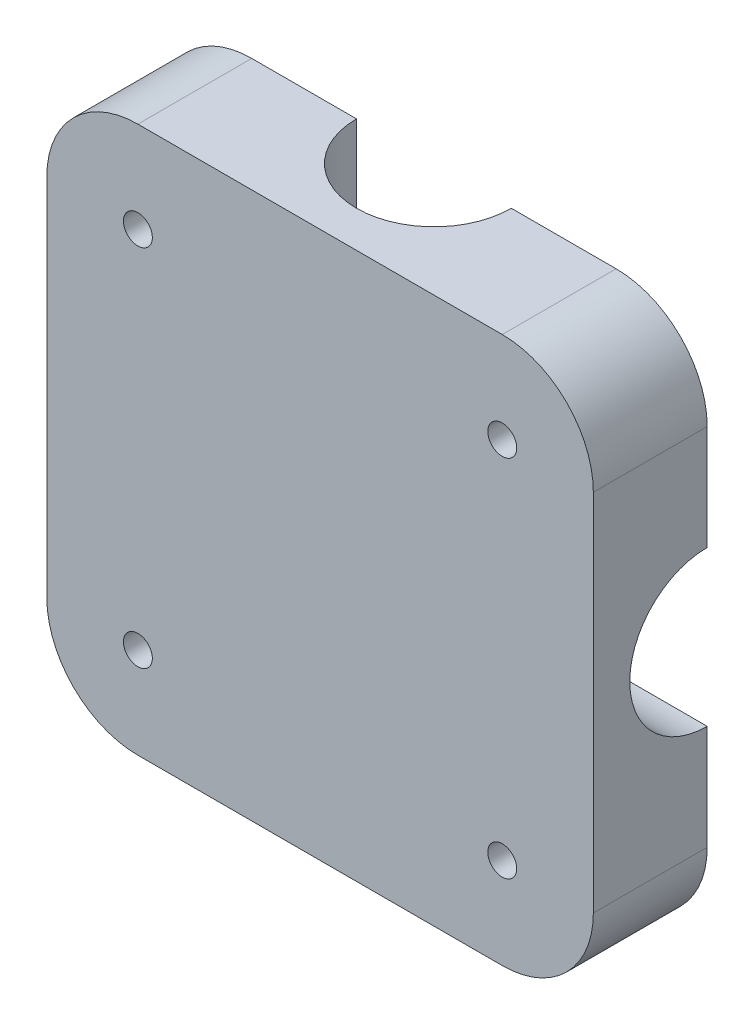
SolidWorks part; units mm, degrees
ref_plane "Alzado" through (0, 0, 0) normal (0, 0, 1) x (1, 0, 0)
ref_plane "Planta" through (0, 0, 0) normal (0, 1, 0) x (1, 0, 0)
ref_plane "Vista lateral" through (0, 0, 0) normal (1, 0, 0) x (0, 0, -1)
sketch "Croquis1" plane through (0, 0, 0) normal (0, 0, 1) x (1, 0, 0)
  line L1 (-20, -30) -> (20, -30)
  line L2 (-30, -20) -> (-30, 20)
  line L3 (-20, 30) -> (20, 30)
  line L4 (30, -20) -> (30, 20)
  line L5 (-30, -30) -> (30, 30) construction
  line L6 (-30, 30) -> (30, -30) construction
  arc A0 (20, 30) -> (30, 20) centre (20, 20) cw
  arc A1 (20, -30) -> (30, -20) centre (20, -20) ccw
  arc A2 (-20, -30) -> (-30, -20) centre (-20, -20) cw
  arc A3 (-30, 20) -> (-20, 30) centre (-20, 20) cw
  point P0 (0, 0)
  dimension "D3" = 10
  dimension "D1" = 60
  dimension "D2" = 60
extrude "Saliente-Extruir1" add sketch "Croquis1" along normal blind 12.5
sketch "Croquis2" plane through (0, 0, 0) normal (0, 1, 0) x (1, 0, 0)
  circle A0 centre (0, 0) radius 8.5
  dimension "D1" = 17
extrude "Cortar-Extruir1" cut sketch "Croquis2" against normal mid plane 82.5
sketch "Croquis3" plane through (-30, 0, 0) normal (-1, 0, 0) x (0, 0, 1)
  circle A0 centre (0, 0) radius 8.5
  dimension "D1" = 17
extrude "Cortar-Extruir2" cut sketch "Croquis3" against normal blind 82.5
sketch "Croquis4" plane through (0, 0, 12.5) normal (0, 0, 1) x (1, 0, 0)
  line L0 (-20, 20) -> (20, 20) construction
  line L1 (-20, 20) -> (-20, -20) construction
  circle A0 centre (-20, 20) radius 1.5875
  circle A1 centre (20, 20) radius 1.5875
  circle A2 centre (20, -20) radius 1.5875
  circle A3 centre (-20, -20) radius 1.5875
  dimension "D1" = 3.175
  dimension "D4" = 40
  dimension "D5" = 40
  dimension "D6" = 20
  dimension "D2" = 2
  dimension "D3" = 2
extrude "Cortar-Extruir3" cut sketch "Croquis4" against normal blind 82.5
